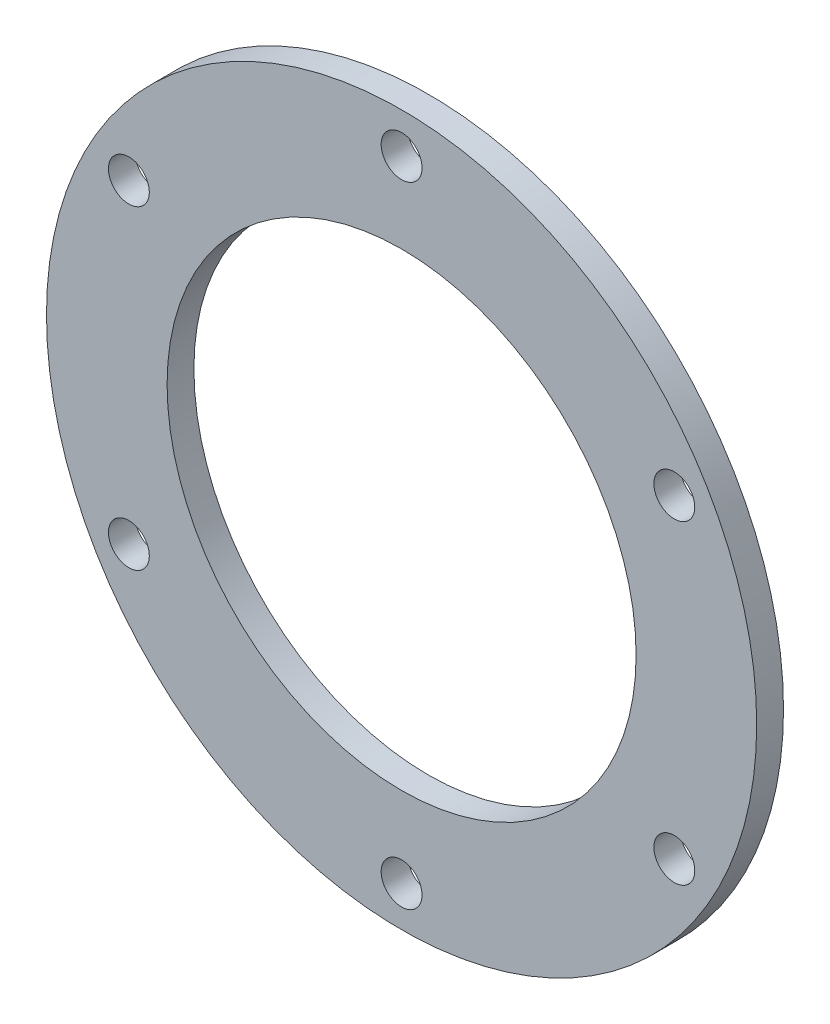
SolidWorks part; units mm, degrees
material "Thornel Mat VMA"
ref_plane "前视基准面" through (0, 0, 0) normal (0, 0, 1) x (1, 0, 0)
ref_plane "上视基准面" through (0, 0, 0) normal (0, 1, 0) x (1, 0, 0)
ref_plane "右视基准面" through (0, 0, 0) normal (1, 0, 0) x (0, 0, -1)
other "Configuration Table"
sketch "草图1" plane through (0, 0, 0) normal (0, 0, 1) x (1, 0, 0)
  circle A0 centre (0, 0) radius 26.5
  circle A1 centre (0, 0) radius 20 construction
  circle A2 centre (0, 0) radius 17.5
  dimension "D1" = 53
  dimension "D2" = 40
  dimension "D3" = 2.5
extrude "凸台-拉伸1" add sketch "草图1" along normal blind 2
sketch "草图2" plane through (0, 0, 2) normal (0, 0, 1) x (1, 0, 0)
  circle A0 centre (0, 0) radius 23.5 construction
  circle A1 centre (0, 0) radius 26.5 construction
  circle A2 centre (0, 23.5) radius 1.525
  circle A3 centre (20.3516, 11.75) radius 1.525
  circle A4 centre (20.3516, -11.75) radius 1.525
  circle A5 centre (0, -23.5) radius 1.525
  circle A6 centre (-20.3516, -11.75) radius 1.525
  circle A7 centre (-20.3516, 11.75) radius 1.525
  point P19 (0, 0)
  dimension "D1" = 3
  dimension "D2" = 3.05
  dimension "D3" = 6
extrude "切除-拉伸1" cut sketch "草图2" against normal blind 2
